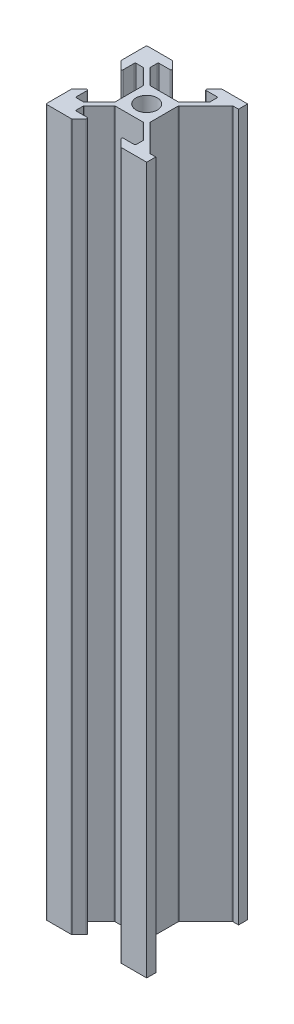
SolidWorks part; units mm, degrees
ref_plane "前视基准面" through (0, 0, 0) normal (0, 0, 1) x (1, 0, 0)
ref_plane "上视基准面" through (0, 0, 0) normal (0, 1, 0) x (1, 0, 0)
ref_plane "右视基准面" through (0, 0, 0) normal (1, 0, 0) x (0, 0, -1)
sketch "草图1" plane through (0, 0, 0) normal (0, 1, 0) x (1, 0, 0)
  line L0 (-25.721, 0) -> (73.7722, 0)
  line L1 (0, 21.255) -> (0, -16.6235)
  line L2 (-10, 21.255) -> (-10, -16.6235)
  line L3 (-25.721, 10) -> (73.7722, 10)
  line L4 (-4.9, 10) -> (-3.1, 8.2)
  line L5 (-3.1, 8.2) -> (-5.9236, 8.2)
  line L6 (-5.9236, 8.2) -> (-5.9236, 6.56)
  line L7 (-5.9236, 6.56) -> (-2.84, 3.4764)
  line L8 (-2.84, 3.4764) -> (2.84, 3.4764)
  line L9 (-10, 10) -> (0, 0) construction
  line L10 (5.9236, 6.56) -> (2.84, 3.4764)
  line L11 (5.9236, 8.2) -> (5.9236, 6.56)
  line L12 (3.1, 8.2) -> (5.9236, 8.2)
  line L13 (4.9, 10) -> (3.1, 8.2)
  line L14 (-10, -4.9) -> (-8.2, -3.1)
  line L15 (-8.2, -3.1) -> (-8.2, -5.9236)
  line L16 (-8.2, -5.9236) -> (-6.56, -5.9236)
  line L17 (-6.56, -5.9236) -> (-3.4764, -2.84)
  line L18 (-3.4764, 2.84) -> (-3.4764, -2.84)
  line L19 (-6.56, 5.9236) -> (-3.4764, 2.84)
  line L20 (-8.2, 5.9236) -> (-6.56, 5.9236)
  line L21 (-8.2, 3.1) -> (-8.2, 5.9236)
  line L22 (-10, 4.9) -> (-8.2, 3.1)
  line L23 (-25.721, -10) -> (73.7722, -10)
  line L24 (4.9, -10) -> (3.1, -8.2)
  line L25 (3.1, -8.2) -> (5.9236, -8.2)
  line L26 (5.9236, -8.2) -> (5.9236, -6.56)
  line L27 (5.9236, -6.56) -> (2.84, -3.4764)
  line L28 (-2.84, -3.4764) -> (2.84, -3.4764)
  line L29 (-5.9236, -6.56) -> (-2.84, -3.4764)
  line L30 (-5.9236, -8.2) -> (-5.9236, -6.56)
  line L31 (-3.1, -8.2) -> (-5.9236, -8.2)
  line L32 (-4.9, -10) -> (-3.1, -8.2)
  line L33 (50, 21.255) -> (50, -16.6235)
  line L34 (20, 21.255) -> (20, -16.6235)
  line L35 (10, 4.9) -> (8.2, 3.1)
  line L36 (8.2, 3.1) -> (8.2, 5.9236)
  line L37 (8.2, 5.9236) -> (6.56, 5.9236)
  line L38 (6.56, 5.9236) -> (3.4764, 2.84)
  line L39 (3.4764, 2.84) -> (3.4764, -2.84)
  line L40 (6.56, -5.9236) -> (3.4764, -2.84)
  line L41 (8.2, -5.9236) -> (6.56, -5.9236)
  line L42 (8.2, -3.1) -> (8.2, -5.9236)
  line L43 (10, -4.9) -> (8.2, -3.1)
  line L44 (15.1, 10) -> (16.9, 8.2)
  line L45 (16.9, 8.2) -> (14.0764, 8.2)
  line L46 (14.0764, 8.2) -> (14.0764, 6.56)
  line L47 (14.0764, 6.56) -> (17.16, 3.4764)
  line L48 (17.16, 3.4764) -> (22.84, 3.4764)
  line L49 (25.9236, 6.56) -> (22.84, 3.4764)
  line L50 (25.9236, 8.2) -> (25.9236, 6.56)
  line L51 (23.1, 8.2) -> (25.9236, 8.2)
  line L52 (24.9, 10) -> (23.1, 8.2)
  line L53 (10, -4.9) -> (11.8, -3.1)
  line L54 (11.8, -3.1) -> (11.8, -5.9236)
  line L55 (11.8, -5.9236) -> (13.44, -5.9236)
  line L56 (13.44, -5.9236) -> (16.5236, -2.84)
  line L57 (16.5236, 2.84) -> (16.5236, -2.84)
  line L58 (13.44, 5.9236) -> (16.5236, 2.84)
  line L59 (11.8, 5.9236) -> (13.44, 5.9236)
  line L60 (11.8, 3.1) -> (11.8, 5.9236)
  line L61 (10, 4.9) -> (11.8, 3.1)
  line L62 (24.9, -10) -> (23.1, -8.2)
  line L63 (23.1, -8.2) -> (25.9236, -8.2)
  line L64 (25.9236, -8.2) -> (25.9236, -6.56)
  line L65 (25.9236, -6.56) -> (22.84, -3.4764)
  line L66 (17.16, -3.4764) -> (22.84, -3.4764)
  line L67 (14.0764, -6.56) -> (17.16, -3.4764)
  line L68 (14.0764, -8.2) -> (14.0764, -6.56)
  line L69 (16.9, -8.2) -> (14.0764, -8.2)
  line L70 (15.1, -10) -> (16.9, -8.2)
  line L71 (30, 4.9) -> (28.2, 3.1)
  line L72 (28.2, 3.1) -> (28.2, 5.9236)
  line L73 (28.2, 5.9236) -> (26.56, 5.9236)
  line L74 (26.56, 5.9236) -> (23.4764, 2.84)
  line L75 (23.4764, 2.84) -> (23.4764, -2.84)
  line L76 (26.56, -5.9236) -> (23.4764, -2.84)
  line L77 (28.2, -5.9236) -> (26.56, -5.9236)
  line L78 (28.2, -3.1) -> (28.2, -5.9236)
  line L79 (30, -4.9) -> (28.2, -3.1)
  line L80 (6.56, 5.9236) -> (8.8364, 8.2)
  line L81 (35.1, 10) -> (36.9, 8.2)
  line L82 (36.9, 8.2) -> (34.0764, 8.2)
  line L83 (34.0764, 8.2) -> (34.0764, 6.56)
  line L84 (34.0764, 6.56) -> (37.16, 3.4764)
  line L85 (37.16, 3.4764) -> (42.84, 3.4764)
  line L86 (45.9236, 6.56) -> (42.84, 3.4764)
  line L87 (45.9236, 8.2) -> (45.9236, 6.56)
  line L88 (43.1, 8.2) -> (45.9236, 8.2)
  line L89 (44.9, 10) -> (43.1, 8.2)
  line L90 (30, -4.9) -> (31.8, -3.1)
  line L91 (31.8, -3.1) -> (31.8, -5.9236)
  line L92 (31.8, -5.9236) -> (33.44, -5.9236)
  line L93 (33.44, -5.9236) -> (36.5236, -2.84)
  line L94 (36.5236, 2.84) -> (36.5236, -2.84)
  line L95 (33.44, 5.9236) -> (36.5236, 2.84)
  line L96 (31.8, 5.9236) -> (33.44, 5.9236)
  line L97 (31.8, 3.1) -> (31.8, 5.9236)
  line L98 (30, 4.9) -> (31.8, 3.1)
  line L99 (44.9, -10) -> (43.1, -8.2)
  line L100 (43.1, -8.2) -> (45.9236, -8.2)
  line L101 (45.9236, -8.2) -> (45.9236, -6.56)
  line L102 (45.9236, -6.56) -> (42.84, -3.4764)
  line L103 (37.16, -3.4764) -> (42.84, -3.4764)
  line L104 (34.0764, -6.56) -> (37.16, -3.4764)
  line L105 (34.0764, -8.2) -> (34.0764, -6.56)
  line L106 (36.9, -8.2) -> (34.0764, -8.2)
  line L107 (35.1, -10) -> (36.9, -8.2)
  line L108 (50, 4.9) -> (48.2, 3.1)
  line L109 (48.2, 3.1) -> (48.2, 5.9236)
  line L110 (48.2, 5.9236) -> (46.56, 5.9236)
  line L111 (46.56, 5.9236) -> (43.4764, 2.84)
  line L112 (43.4764, 2.84) -> (43.4764, -2.84)
  line L113 (46.56, -5.9236) -> (43.4764, -2.84)
  line L114 (48.2, -5.9236) -> (46.56, -5.9236)
  line L115 (48.2, -3.1) -> (48.2, -5.9236)
  line L116 (50, -4.9) -> (48.2, -3.1)
  line L117 (13.44, 5.9236) -> (11.1636, 8.2)
  line L118 (30, 10) -> (40, 0) construction
  line L119 (10, 10) -> (20, 0) construction
  line L120 (8.8364, 8.2) -> (11.1636, 8.2)
  line L121 (8.8364, -8.2) -> (11.1636, -8.2)
  line L122 (6.56, -5.9236) -> (8.8364, -8.2)
  line L123 (13.44, -5.9236) -> (11.1636, -8.2)
  line L124 (26.56, 5.9236) -> (28.8364, 8.2)
  line L125 (28.8364, 8.2) -> (31.1636, 8.2)
  line L126 (33.44, 5.9236) -> (31.1636, 8.2)
  line L127 (26.56, -5.9236) -> (28.8364, -8.2)
  line L128 (28.8364, -8.2) -> (31.1636, -8.2)
  line L129 (33.44, -5.9236) -> (31.1636, -8.2)
  circle A0 centre (0, 0) radius 2.1
  circle A1 centre (20, 0) radius 2.1
  circle A2 centre (40, 0) radius 2.1
  circle A3 centre (20, 0) radius 2.1
  circle A4 centre (40, 0) radius 2.1
  point P22 (0, 3.4764)
  point P37 (-3.4764, 0)
  point P50 (0, -3.4764)
  point P65 (3.4764, 0)
  point P77 (20, 3.4764)
  point P92 (16.5236, 0)
  point P103 (20, -3.4764)
  point P114 (23.4764, 0)
  point P124 (40, 3.4764)
  point P139 (36.5236, 0)
  point P150 (40, -3.4764)
  point P161 (43.4764, 0)
  dimension "D1" = 3
  dimension "D2" = 4.2
  dimension "D3" = 20
  dimension "D6" = 1.8
  dimension "D7" = 1.64
  dimension "D8" = 2.84
  dimension "D9" = 3.1
  dimension "D10" = 45
  dimension "D11" = 0.9
  dimension "D16" = 2
  dimension "D4" = 10
  dimension "D5" = 10
  dimension "D12" = 10
  dimension "D13" = 60
  dimension "D14" = 30
  dimension "D15" = 3
extrude "凸台-拉伸1" add sketch "草图1" along normal blind 140 contours A0 L1 L8 L7 L6 L5 L4 L3 L2 L22 L21 L20 L19 L18 L0 | A0 L0 L18 L17 L16 L15 L14 L2 L23 L32 L31 L30 L29 L28 L1 | A1 L0 L57 L56 L123 L121 L122 L40 L39 A0 L1 L28 L27 L26 L25 L24 L23 L70 L69 L68 L67 L66 L34 | A1 L34 L48 L47 L46 L45 L44 L3 L13 L12 L11 L10 L8 L1 A0 L0 L39 L38 L80 L120 L117 L58 L57 | A2 L0 L112 L111 L110 L109 L108 L33 L3 L89 L88 L87 L86 L85 L84 L83 L82 L81 L52 L51 L50 L49 L48 L34 A1 L75 L74 L124 L125 L126 L95 L94 | A2 L0 L94 L93 L129 L128 L127 L76 L75 A1 L34 L66 L65 L64 L63 L62 L23 L107 L106 L105 L104 L103 L102 L101 L100 L99 L33 L116 L115 L114 L113 L112
fillet "圆角1" radius 0.2 100 edges at (8.8364, 70, 8.2) (11.1636, 70, 8.2) (16.5236, 70, 2.84) (16.5236, 70, -2.84) (11.1636, 70, -8.2) (8.8364, 70, -8.2) (3.4764, 70, -2.84) (3.4764, 70, 2.84) (28.8364, 70, 8.2) (31.1636, 70, 8.2) (36.5236, 70, 2.84) (36.5236, 70, -2.84) (31.1636, 70, -8.2) (28.8364, 70, -8.2) (23.4764, 70, -2.84) (23.4764, 70, 2.84) (46.56, 70, 5.9236) (48.2, 70, 5.9236) (48.2, 70, 3.1) (50, 70, 4.9) (50, 70, 10) (44.9, 70, 10) (43.1, 70, 8.2) (45.9236, 70, 8.2) (45.9236, 70, 6.56) (42.84, 70, 3.4764) (37.16, 70, 3.4764) (34.0764, 70, 6.56) (34.0764, 70, 8.2) (36.9, 70, 8.2) (35.1, 70, 10) (24.9, 70, 10) (23.1, 70, 8.2) (25.9236, 70, 8.2) (25.9236, 70, 6.56) (22.84, 70, 3.4764) (17.16, 70, 3.4764) (14.0764, 70, 6.56) (14.0764, 70, 8.2) (16.9, 70, 8.2) (15.1, 70, 10) (4.9, 70, 10) (3.1, 70, 8.2) (5.9236, 70, 8.2) (5.9236, 70, 6.56) (2.84, 70, 3.4764) (-2.84, 70, 3.4764) (-5.9236, 70, 6.56) (-5.9236, 70, 8.2) (-3.1, 70, 8.2) (-4.9, 70, 10) (-10, 70, 10) (-10, 70, 4.9) (-8.2, 70, 3.1) (-8.2, 70, 5.9236) (-6.56, 70, 5.9236) (-3.4764, 70, 2.84) (-3.4764, 70, -2.84) (-6.56, 70, -5.9236) (-8.2, 70, -5.9236) (-8.2, 70, -3.1) (-10, 70, -4.9) (-10, 70, -10) (-4.9, 70, -10) (-3.1, 70, -8.2) (-5.9236, 70, -8.2) (-5.9236, 70, -6.56) (-2.84, 70, -3.4764) (2.84, 70, -3.4764) (5.9236, 70, -6.56) (5.9236, 70, -8.2) (3.1, 70, -8.2) (4.9, 70, -10) (15.1, 70, -10) (16.9, 70, -8.2) (14.0764, 70, -8.2) (14.0764, 70, -6.56) (17.16, 70, -3.4764) (22.84, 70, -3.4764) (25.9236, 70, -6.56) (25.9236, 70, -8.2) (23.1, 70, -8.2) (24.9, 70, -10) (35.1, 70, -10) (36.9, 70, -8.2) (34.0764, 70, -8.2) (34.0764, 70, -6.56) (37.16, 70, -3.4764) (42.84, 70, -3.4764) (45.9236, 70, -6.56) (45.9236, 70, -8.2) (43.1, 70, -8.2) (44.9, 70, -10) (50, 70, -4.9) (48.2, 70, -3.1) (48.2, 70, -5.9236) (46.56, 70, -5.9236) (43.4764, 70, -2.84) (43.4764, 70, 2.84) (50, 70, -10)
sketch "草图2" plane through (0, 0, 0) normal (0, -1, 0) x (1, 0, 0)
  line L0 (4.9828, 10) -> (15.0172, 10) construction
  line L1 (10, 10) -> (51.4166, 10)
  line L2 (10, 10) -> (10, -11.8553)
  line L3 (10, -11.8553) -> (51.4166, -11.8553)
  line L4 (51.4166, 10) -> (51.4166, -11.8553)
extrude "切除-拉伸1" cut sketch "草图2" against normal through all both and the other way through all
